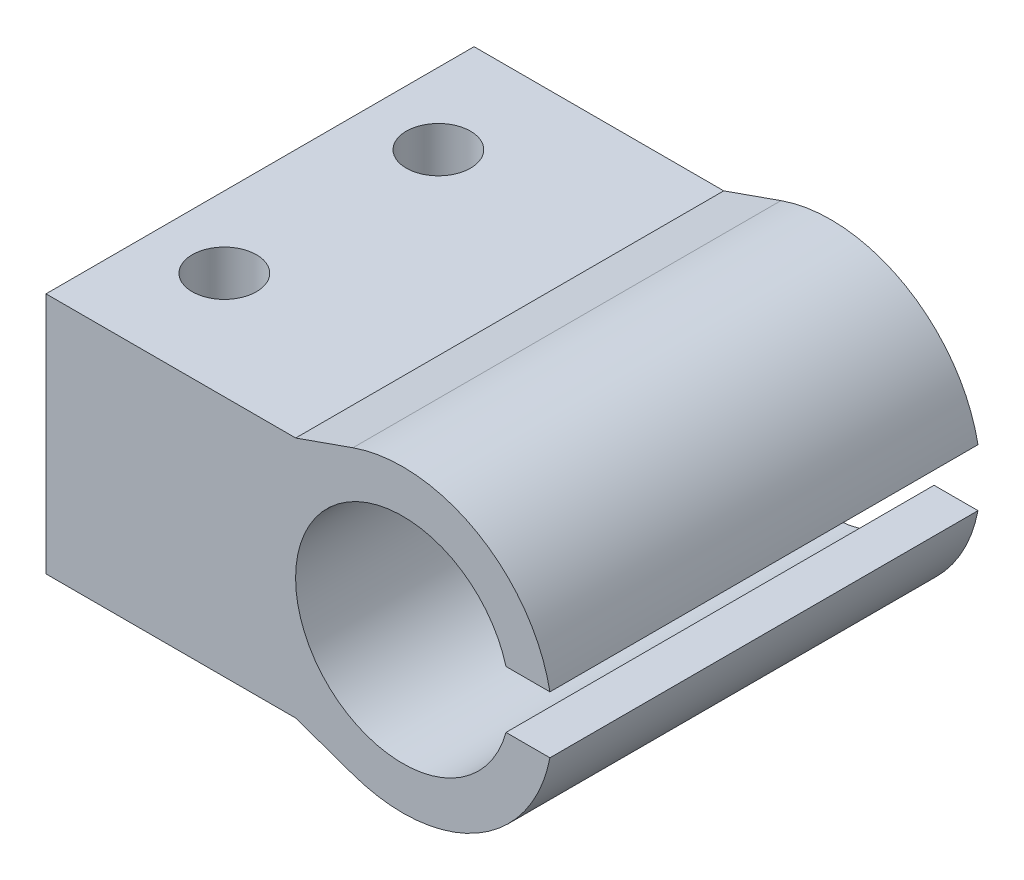
SolidWorks part; units mm, degrees
ref_plane "前视基准面" through (0, 0, 0) normal (0, 0, 1) x (1, 0, 0)
ref_plane "上视基准面" through (0, 0, 0) normal (0, 1, 0) x (1, 0, 0)
ref_plane "右视基准面" through (0, 0, 0) normal (1, 0, 0) x (0, 0, -1)
sketch "草图1" plane through (0, 0, 0) normal (0, 0, 1) x (1, 0, 0)
  line B0 (-20, 8.5) -> (-20, -8.5)
  line B1 (-22.25, 8.5) -> (-22.25, -8.5)
  line B2 (-17.75, 8.5) -> (-17.75, -8.5)
  line B3 (-25, 8.5) -> (-25, -8.5)
  line B4 (7.2371, -2) -> (10.3163, -2)
  line B5 (7.2371, 2) -> (10.3163, 2)
  line B6 (-25, -8.5) -> (-7.5, -8.5)
  line B7 (-25, 8.5) -> (-7.5, 8.5)
  line B8 (-7.5, 8.5) -> (-3.49, 9.9119)
  line B9 (-7.5, -8.5) -> (-3.49, -9.9119)
  arc B10 (7.2371, 2) -> (7.2371, -2) centre (0, 0) ccw
  arc B11 (-3.49, -9.9119) -> (10.3163, -2) centre (0, 0) ccw
  arc B12 (10.3163, 2) -> (-3.49, 9.9119) centre (0, 0) ccw
sketch_block_instance "块1-1"
sketch_block "块1"
sketch "草图2" plane through (0, 0, 0) normal (0, 0, 1) x (1, 0, 0)
  line L0 (-25, 8.5) -> (-7.5, 8.5) construction
  line L1 (-7.5, 8.5) -> (-3.49, 9.9119) construction
  line L2 (7.2371, 2) -> (10.3163, 2) construction
  line L3 (7.2371, -2) -> (10.3163, -2) construction
  line L4 (-7.5, -8.5) -> (-3.49, -9.9119) construction
  line L5 (-25, -8.5) -> (-7.5, -8.5) construction
  line L6 (-25, 8.5) -> (-25, -8.5) construction
  line L7 (-25, 8.5) -> (-7.5, 8.5)
  line L8 (-7.5, 8.5) -> (-3.49, 9.9119)
  line L9 (7.2371, 2) -> (10.3163, 2)
  line L10 (7.2371, -2) -> (10.3163, -2)
  line L11 (-7.5, -8.5) -> (-3.49, -9.9119)
  line L12 (-25, -8.5) -> (-7.5, -8.5)
  line L13 (-25, 8.5) -> (-25, -8.5)
  arc A0 (10.3163, 2) -> (-3.49, 9.9119) centre (0, 0) ccw construction
  arc A1 (7.2371, 2) -> (7.2371, -2) centre (0, 0) ccw construction
  arc A2 (-3.49, -9.9119) -> (10.3163, -2) centre (0, 0) ccw construction
  arc A3 (10.3163, 2) -> (-3.49, 9.9119) centre (0, 0) ccw
  arc A4 (7.2371, 2) -> (7.2371, -2) centre (0, 0) ccw
  arc A5 (-3.49, -9.9119) -> (10.3163, -2) centre (0, 0) ccw
extrude "凸台-拉伸1" add sketch "草图2" along normal blind 30
sketch "草图3" plane through (0, -8.5, 0) normal (0, -1, 0) x (1, 0, 0)
  line L0 (-25, 30) -> (-7.5, 30) construction
  line L1 (-25, 0) -> (-7.5, 0) construction
  line L2 (-25, 30) -> (-25, 0) construction
  circle A0 centre (-20, 7.5) radius 2.25
  circle A1 centre (-20, 22.5) radius 2.25
  dimension "D3" = 4.5
  dimension "D1" = 7.5
  dimension "D2" = 7.5
  dimension "D4" = 5
extrude "切除-拉伸1" cut sketch "草图3" against normal through all
